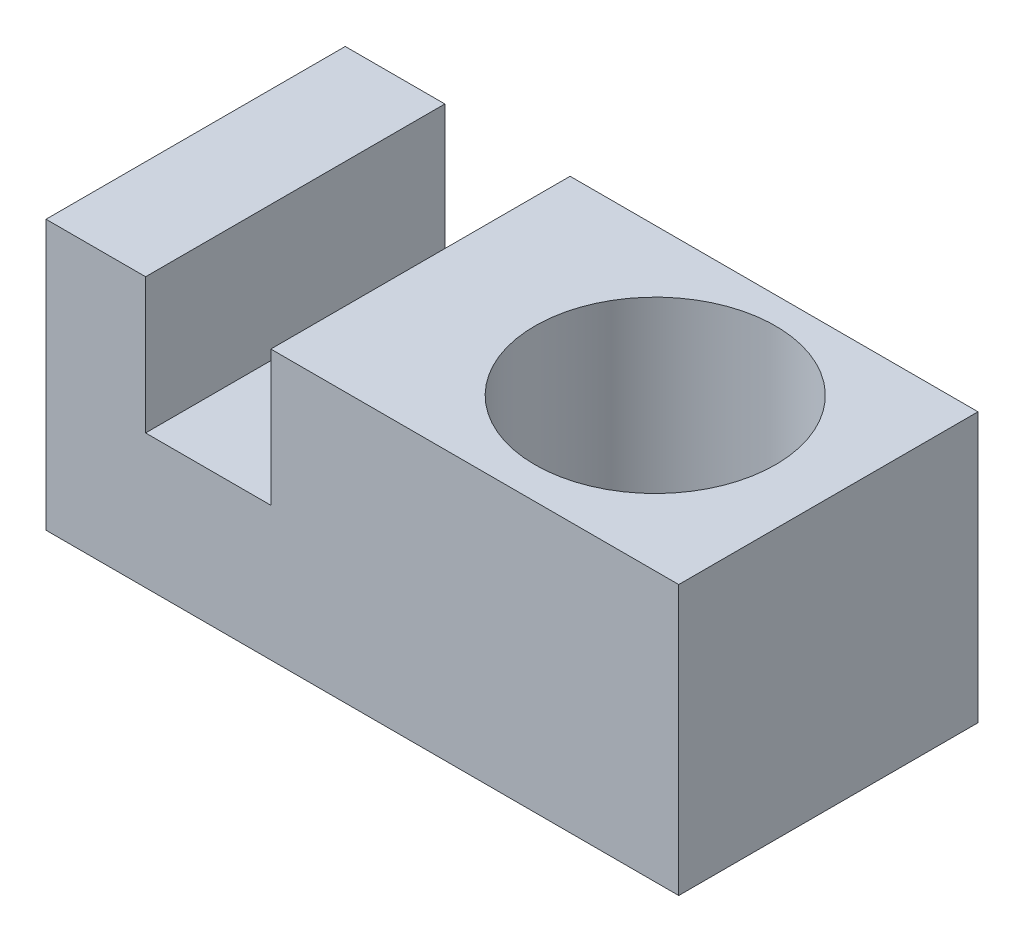
SolidWorks part; units mm, degrees
ref_plane "Front Plane" through (0, 0, 0) normal (0, 0, 1) x (1, 0, 0)
ref_plane "Top Plane" through (0, 0, 0) normal (0, 1, 0) x (1, 0, 0)
ref_plane "Right Plane" through (0, 0, 0) normal (1, 0, 0) x (0, 0, -1)
sketch "Sketch1" plane through (0, 0, 0) normal (0, 1, 0) x (1, 0, 0)
  line L1 (0, 0) -> (42.2857, 0)
  line L2 (0, 0) -> (0, 20)
  line L3 (0, 20) -> (42.2857, 20)
  line L4 (42.2857, 0) -> (42.2857, 20)
  dimension "D1" = 20
extrude "Boss-Extrude1" add sketch "Sketch1" along normal blind 18
sketch "Sketch2" plane through (0, 18, 0) normal (0, 1, 0) x (1, 0, 0)
  circle A0 centre (30.5494, 10.1658) radius 8.0389
extrude "Cut-Extrude1" cut sketch "Sketch2" against normal blind 18
sketch "Sketch4" plane through (0, 0, 0) normal (0, 0, 1) x (1, 0, 0)
  line L0 (0, 18) -> (42.2857, 18) construction
  line L1 (6.6561, 18) -> (15.0247, 18)
  line L2 (6.6561, 18) -> (6.6561, 8.9589)
  line L3 (6.6561, 8.9589) -> (15.0247, 8.9589)
  line L4 (15.0247, 18) -> (15.0247, 8.9589)
extrude "Cut-Extrude2" cut sketch "Sketch4" against normal blind 20
